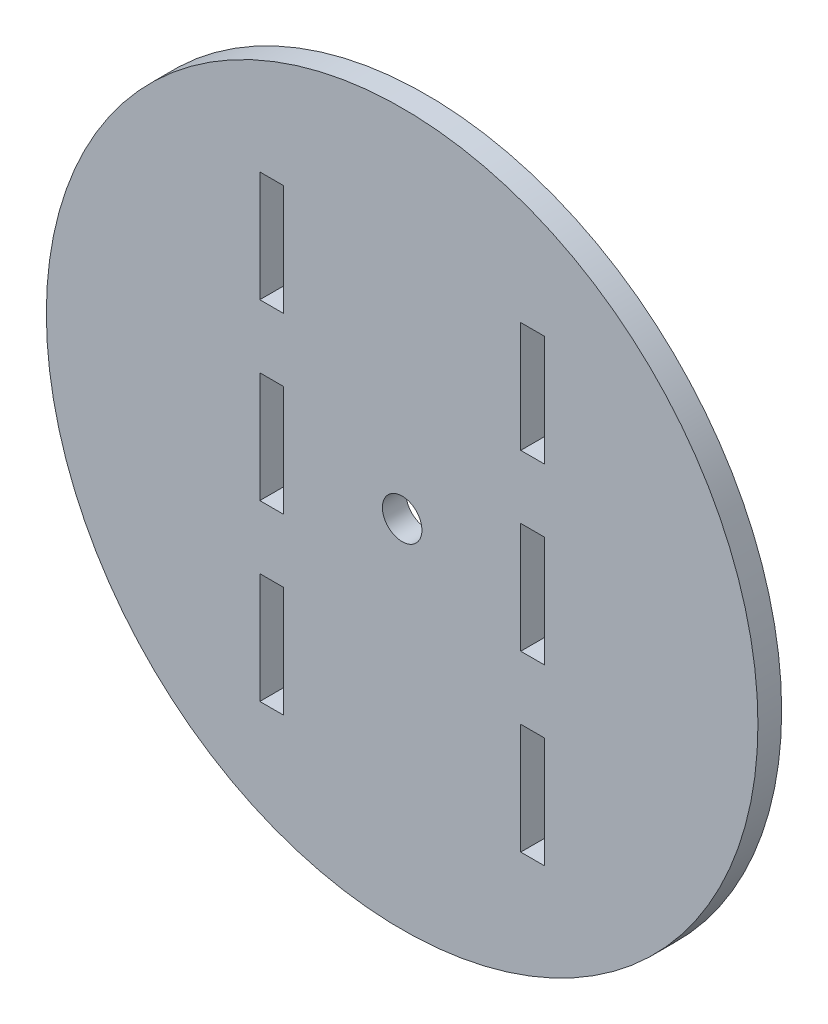
SolidWorks part; units mm, degrees
material "Oak"
ref_plane "Front Plane" through (0, 0, 0) normal (0, 0, 1) x (1, 0, 0)
ref_plane "Top Plane" through (0, 0, 0) normal (0, 1, 0) x (1, 0, 0)
ref_plane "Right Plane" through (0, 0, 0) normal (1, 0, 0) x (0, 0, -1)
sketch "Sketch1" plane through (0, 0, 0) normal (0, 0, 1) x (1, 0, 0)
  circle A5 centre (45, 147.5081) radius 45
extrude "Boss-Extrude1" add sketch "Sketch1" along normal blind 3
sketch "Sketch2" plane through (0, 0, 0) normal (0, 0, 1) x (1, 0, 0)
  line L0 (60, 176.5081) -> (60, 162.5081)
  line L1 (60, 140.5081) -> (60, 154.5081)
  line L2 (63, 132.5081) -> (63, 118.5081)
  line L3 (60, 132.5081) -> (60, 118.5081)
  line L4 (63, 176.5081) -> (63, 162.5081)
  line L5 (63, 140.5081) -> (60, 140.5081)
  line L6 (63, 154.5081) -> (63, 140.5081)
  line L7 (60, 154.5081) -> (63, 154.5081)
  line L8 (60, 132.5081) -> (63, 132.5081)
  line L9 (60, 162.5081) -> (63, 162.5081)
  line L10 (63, 118.5081) -> (60, 118.5081)
  line L11 (60, 176.5081) -> (63, 176.5081)
  line L12 (30, 176.5081) -> (30, 162.5081)
  line L13 (27, 162.5081) -> (30, 162.5081)
  line L15 (27, 118.5081) -> (30, 118.5081)
  line L16 (27, 176.5081) -> (30, 176.5081)
  line L17 (27, 140.5081) -> (27, 154.5081)
  line L18 (30, 132.5081) -> (30, 118.5081)
  line L19 (27, 132.5081) -> (27, 118.5081)
  line L20 (27, 162.5081) -> (27, 176.5081)
  line L21 (30, 140.5081) -> (27, 140.5081)
  line L22 (30, 154.5081) -> (30, 140.5081)
  line L23 (27, 154.5081) -> (30, 154.5081)
  line L24 (27, 132.5081) -> (30, 132.5081)
  circle A4 centre (45, 147.5081) radius 2.5
  dimension "D1" = 15
  dimension "D2" = 15
  dimension "D4" = 3
  dimension "D5" = 3
  dimension "D6" = 3
  dimension "D7" = 3
  dimension "D8" = 3
  dimension "D9" = 3
extrude "Cut-Extrude3" cut sketch "Sketch2" along normal blind 35 contours L0 L9 L4 L11 | L1 L7 L6 L5 | L3 L10 L2 L8 | L12 L13 L20 L16 | L22 L21 L17 L23 | L18 L15 L19 L24 | A4
